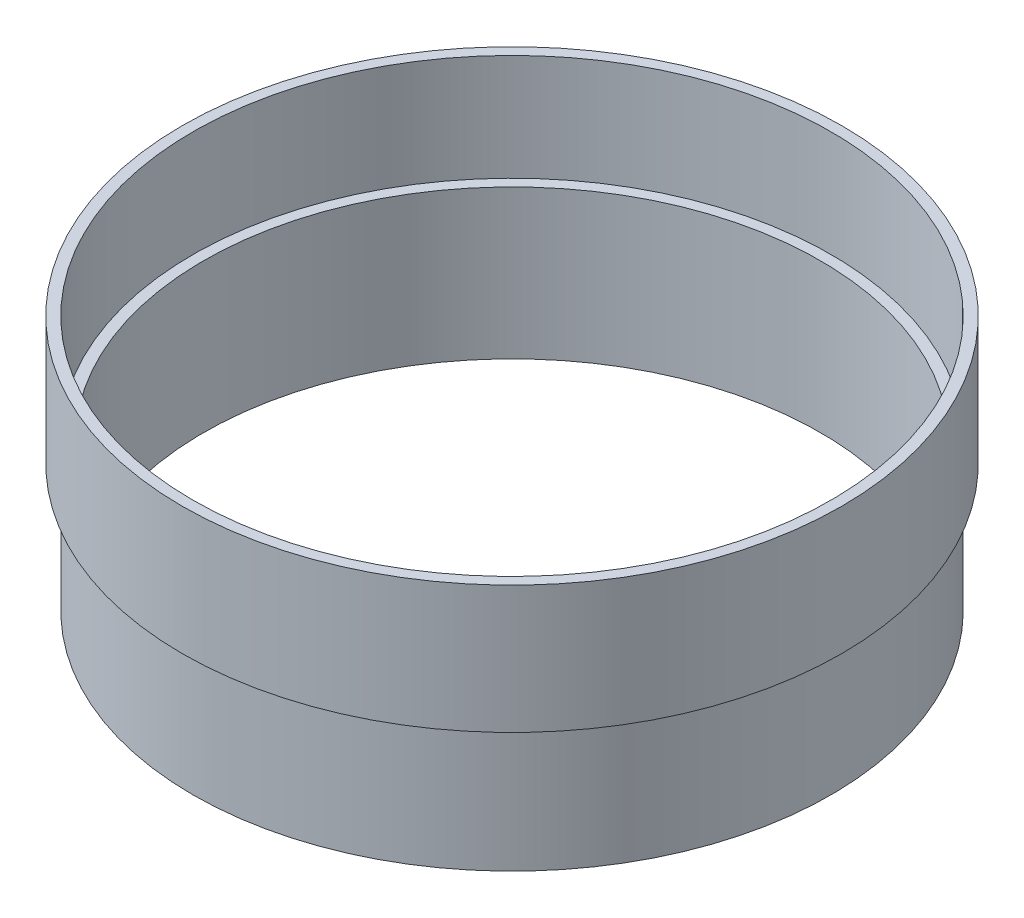
SolidWorks part; units mm, degrees
ref_plane "Front Plane" through (0, 0, 0) normal (0, 0, 1) x (1, 0, 0)
ref_plane "Top Plane" through (0, 0, 0) normal (0, 1, 0) x (1, 0, 0)
ref_plane "Right Plane" through (0, 0, 0) normal (1, 0, 0) x (0, 0, -1)
sketch "Sketch1" plane through (0, 0, 0) normal (0, 1, 0) x (1, 0, 0)
  circle A0 centre (0, 0) radius 14.5
  circle A1 centre (0, 0) radius 15
  dimension "D1" = 29
  dimension "D2" = 30
extrude "Boss-Extrude1" add sketch "Sketch1" along normal blind 6
sketch "Sketch2" plane through (0, 6, 0) normal (0, 1, 0) x (1, 0, 0)
  circle A0 centre (0, 0) radius 14.5
  circle A1 centre (0, 0) radius 15.5
  dimension "D1" = 31
  dimension "D2" = 29
extrude "Boss-Extrude2" add sketch "Sketch2" along normal blind 1
sketch "Sketch3" plane through (0, 7, 0) normal (0, 1, 0) x (1, 0, 0)
  circle A0 centre (0, 0) radius 15.5
  circle A1 centre (0, 0) radius 15
  dimension "D1" = 31
  dimension "D2" = 30
extrude "Boss-Extrude3" add sketch "Sketch3" along normal blind 5
